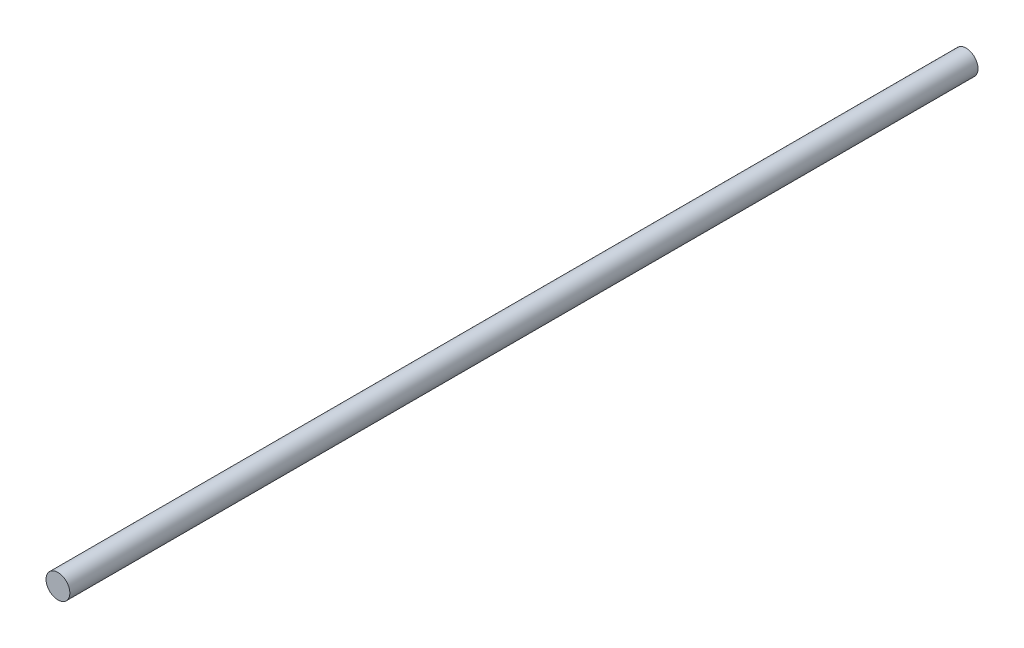
SolidWorks part; units mm, degrees
ref_plane "Front Plane" through (0, 0, 0) normal (0, 0, 1) x (1, 0, 0)
ref_plane "Top Plane" through (0, 0, 0) normal (0, 1, 0) x (1, 0, 0)
ref_plane "Right Plane" through (0, 0, 0) normal (1, 0, 0) x (0, 0, -1)
sketch "Sketch1" plane through (0, 0, 0) normal (0, 0, 1) x (1, 0, 0)
  circle A0 centre (0, 0) radius 6
  dimension "D1" = 12
extrude "Boss-Extrude1" add sketch "Sketch1" along normal blind 457.2
